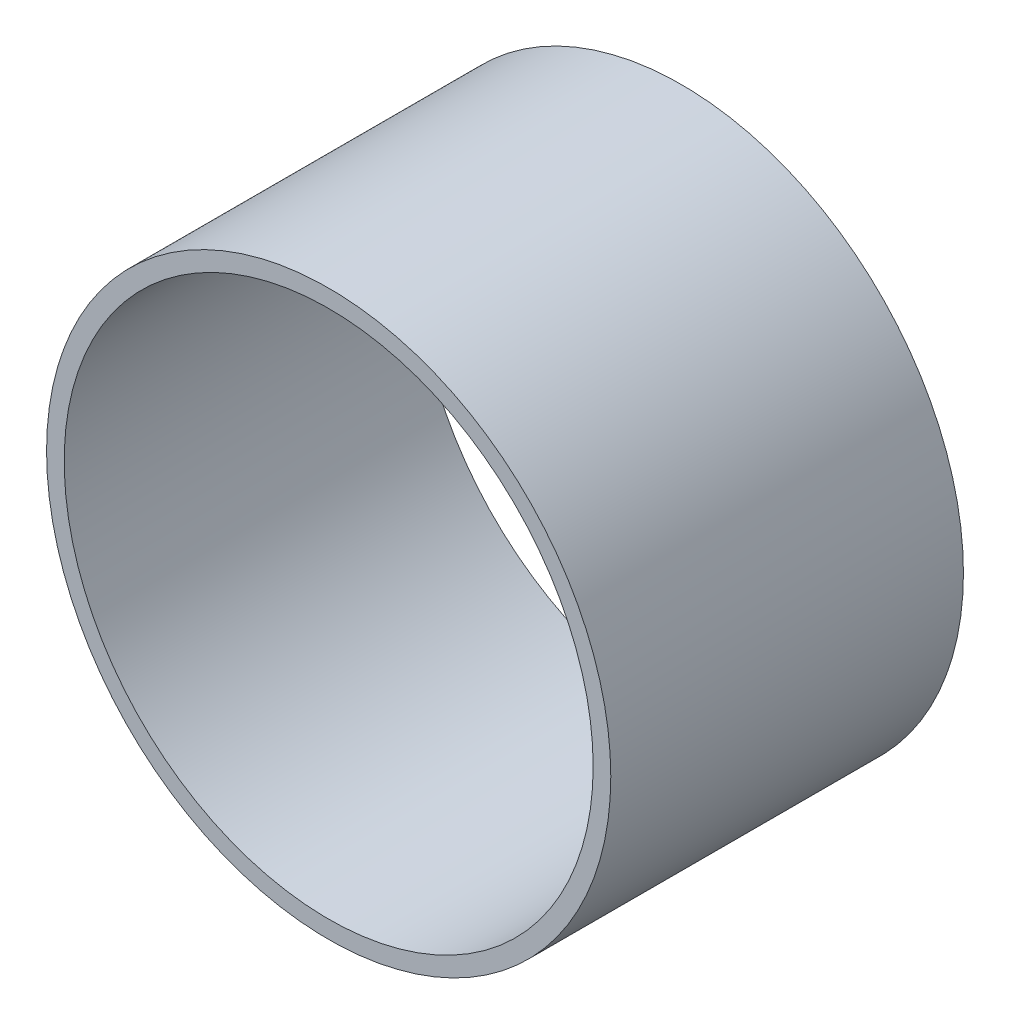
SolidWorks part; units mm, degrees
ref_plane "前视基准面" through (0, 0, 0) normal (0, 0, 1) x (1, 0, 0)
ref_plane "上视基准面" through (0, 0, 0) normal (0, 1, 0) x (1, 0, 0)
ref_plane "右视基准面" through (0, 0, 0) normal (1, 0, 0) x (0, 0, -1)
other "Configuration Table"
sketch "草图1" plane through (0, 0, 0) normal (1, 0, 0) x (0, 0, -1)
  line L0 (136, 0) -> (206, 0) construction
  line L1 (201, 45) -> (201, 48)
  line L2 (201, 48) -> (141, 48)
  line L3 (141, 48) -> (141, 45)
  line L4 (141, 45) -> (201, 45)
revolve "旋转1" add sketch "草图1" angle 360 about L0
